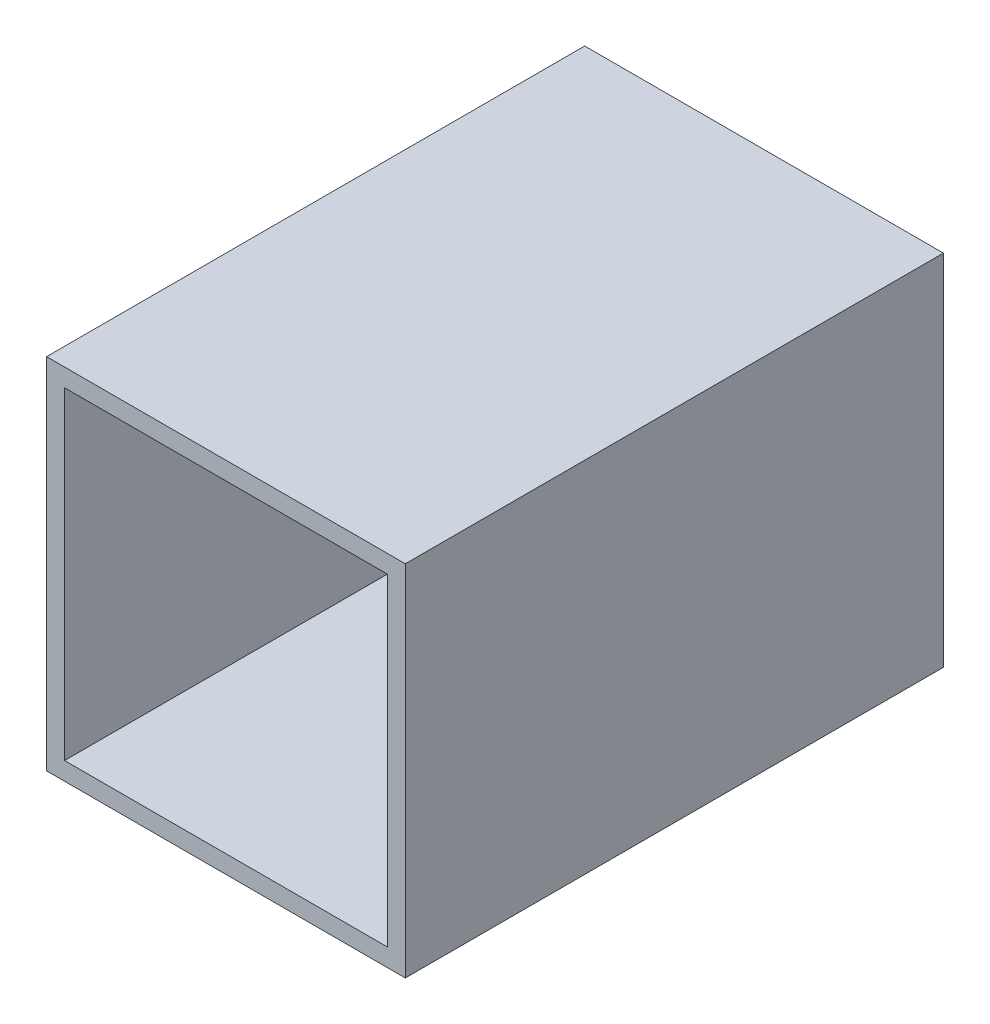
SolidWorks part; units mm, degrees
ref_plane "Plan de face" through (0, 0, 0) normal (0, 0, 1) x (1, 0, 0)
ref_plane "Plan de dessus" through (0, 0, 0) normal (0, 1, 0) x (1, 0, 0)
ref_plane "Plan de droite" through (0, 0, 0) normal (1, 0, 0) x (0, 0, -1)
sketch "Esquisse3" plane through (0, 0, 0) normal (0, 0, 1) x (1, 0, 0)
  line L0 (9, 9) -> (-9, 9)
  line L1 (10, -10) -> (-10, -10)
  line L2 (10, -10) -> (10, 10)
  line L3 (10, 10) -> (-10, 10)
  line L4 (-10, -10) -> (-10, 10)
  line L5 (10, -10) -> (-10, 10) construction
  line L6 (10, 10) -> (-10, -10) construction
  line L7 (-9, -9) -> (-9, 9)
  line L8 (9, -9) -> (-9, -9)
  line L9 (9, -9) -> (9, 9)
  point P0 (0, 0)
  dimension "D1" = 20
  dimension "D2" = 20
  dimension "D3" = 1
extrude "Boss.-Extru.1" add sketch "Esquisse3" along normal blind 30
